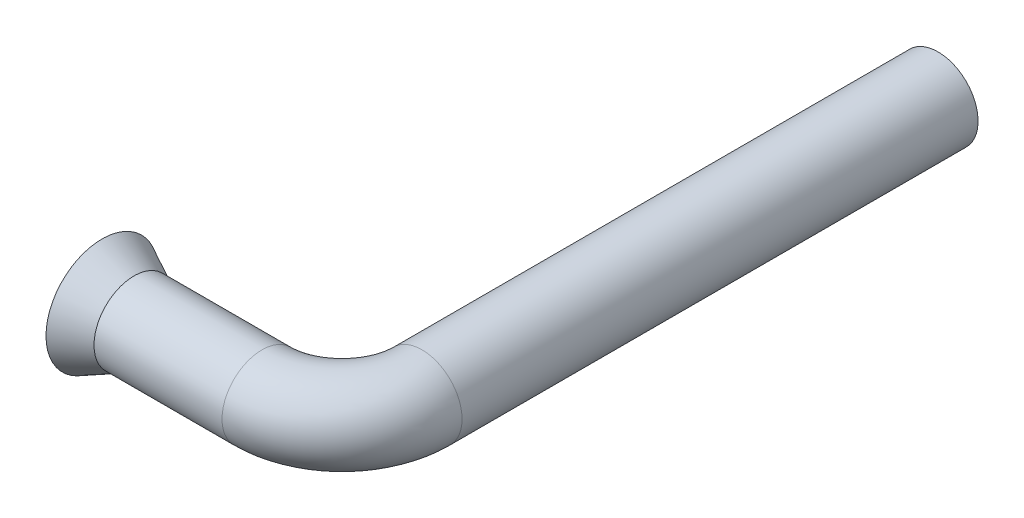
SolidWorks part; units mm, degrees
ref_plane "Спереди" through (0, 0, 0) normal (0, 0, 1) x (1, 0, 0)
ref_plane "Сверху" through (0, 0, 0) normal (0, 1, 0) x (1, 0, 0)
ref_plane "Справа" through (0, 0, 0) normal (1, 0, 0) x (0, 0, -1)
sketch "Эскиз1" plane through (0, 0, 0) normal (0, 1, 0) x (1, 0, 0)
  line L0 (0, 0) -> (20, 0)
  line L1 (30, 10) -> (30, 74.5)
  arc A0 (20, 0) -> (30, 10) centre (20, 10) ccw
  dimension "D1" = 10
sketch "Эскиз2" plane through (0, 0, 0) normal (1, 0, 0) x (0, 0, -1)
  circle A0 centre (0, 0) radius 5
  circle A1 centre (0, 0) radius 4
  dimension "D1" = 10
  dimension "D2" = 8
sweep "По траектории1" add profiles "Эскиз2" path "Эскиз1"
sketch "Эскиз3" plane through (0, 0, 0) normal (0, 0, 1) x (1, 0, 0)
  line L0 (0, 7) -> (0, 4)
  line L1 (0, 7) -> (4, 5)
  line L2 (0, 4) -> (4, 4)
  line L3 (4, 4) -> (4, 5)
  line L4 (-3.4534, 0) -> (12.3837, 0) construction
revolve "Повернуть1" add sketch "Эскиз3" angle 360 about L4
